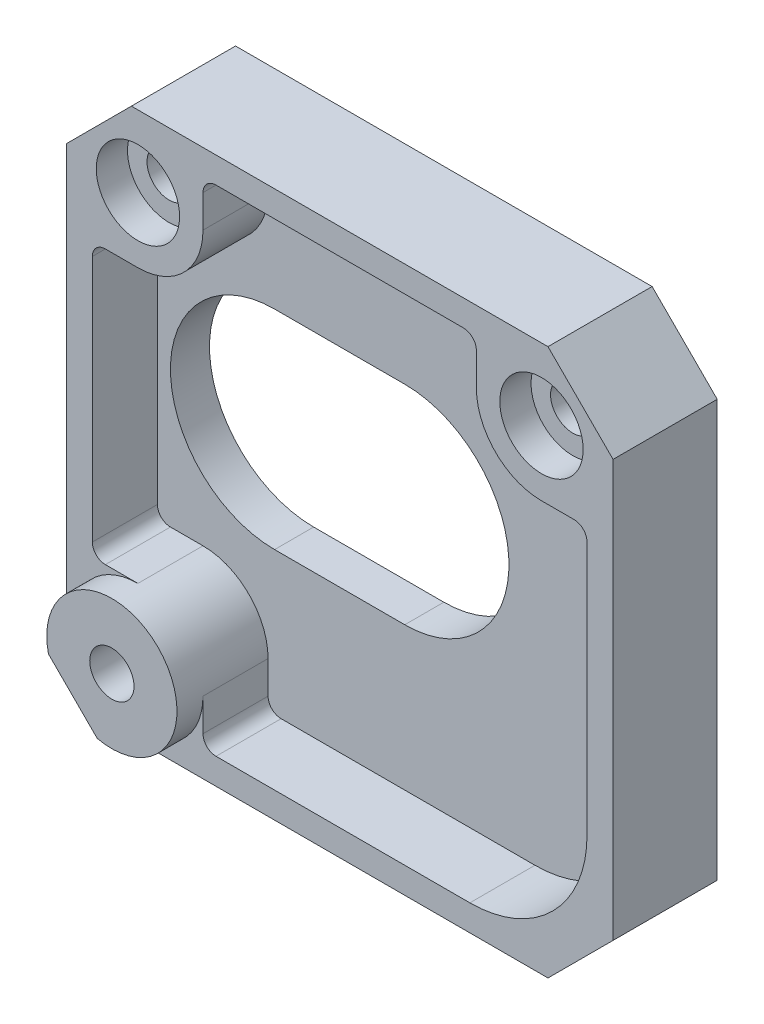
SolidWorks part; units mm, degrees
ref_plane "Спереди" through (0, 0, 0) normal (0, 0, 1) x (1, 0, 0)
ref_plane "Сверху" through (0, 0, 0) normal (0, 1, 0) x (1, 0, 0)
ref_plane "Справа" through (0, 0, 0) normal (1, 0, 0) x (0, 0, -1)
sketch "Эскиз1" plane through (0, 0, 0) normal (0, 0, 1) x (1, 0, 0)
  line L0 (0, 0) -> (-10, 0) construction
  line L1 (21, -21) -> (-21, -21)
  line L2 (21, -21) -> (21, 21)
  line L3 (21, 21) -> (-21, 21)
  line L4 (-21, -21) -> (-21, 21)
  line L5 (21, -21) -> (-21, 21) construction
  line L6 (21, 21) -> (-21, -21) construction
  line L7 (0, -8) -> (-10, -8)
  line L8 (0, 8) -> (-10, 8)
  circle A0 centre (-15.5, -15.5) radius 1.7
  circle A1 centre (-15.5, 15.5) radius 1.7
  circle A2 centre (15.5, 15.5) radius 1.7
  arc A3 (0, -8) -> (0, 8) centre (0, 0) ccw
  arc A4 (-10, 8) -> (-10, -8) centre (-10, 0) ccw
  point P0 (0, 0)
  point P10 (-5, 0)
  point P15 (0, 0)
  point P20 (8, 0)
  point P21 (12.7378, -4.4825)
  point P22 (0, 0)
  point P23 (15.5, 15.5)
  dimension "D3" = 3.4
  dimension "D1" = 42
  dimension "D2" = 42
  dimension "D4" = 15.5
  dimension "D6" = 8
  dimension "D7" = 10
  dimension "D5" = 3
extrude "Бобышка-Вытянуть1" add sketch "Эскиз1" along normal blind 8
chamfer "Фаска1" distance 5 angle 45 4 edges at (-21, -21, 4) (21, -21, 4) (21, 21, 4) (-21, 21, 4)
sketch "Эскиз2" plane through (0, 0, 8) normal (0, 0, 1) x (1, 0, 0)
  line L16 (-10.5, 15.5) -> (-10.5, 19)
  line L17 (-15.5, 10.5) -> (-19, 10.5)
  line L18 (0, 0) -> (0, 19) construction
  line L19 (0, 0) -> (-19, 0) construction
  line L20 (-10.5, -15.5) -> (-10.5, -19)
  line L21 (-15.5, -10.5) -> (-19, -10.5)
  line L22 (10.5, 15.5) -> (10.5, 19)
  line L23 (15.5, 10.5) -> (19, 10.5)
  line L24 (-19, -15.1716) -> (-15.1716, -19)
  line L25 (-15.1716, -19) -> (15.1716, -19)
  line L26 (15.1716, -19) -> (19, -15.1716)
  line L27 (19, -15.1716) -> (19, 15.1716)
  line L28 (19, 15.1716) -> (15.1716, 19)
  line L29 (15.1716, 19) -> (-15.1716, 19)
  line L30 (-15.1716, 19) -> (-19, 15.1716)
  line L31 (-19, 15.1716) -> (-19, -15.1716)
  line L32 (0, 0) -> (18.5, -18.5) construction
  line L33 (-10.5, -19) -> (10, -19)
  line L34 (-21, -16) -> (-16, -21) construction
  line L35 (19, -10) -> (19, 10.5)
  line L36 (16, -21) -> (21, -16) construction
  line L37 (10.5, 19) -> (-10.5, 19)
  line L39 (-19, 10.5) -> (-19, -10.5)
  arc A0 (-15.5, 10.5) -> (-10.5, 15.5) centre (-15.5, 15.5) ccw
  arc A1 (-15.5, -10.5) -> (-10.5, -15.5) centre (-15.5, -15.5) cw
  arc A2 (15.5, 10.5) -> (10.5, 15.5) centre (15.5, 15.5) cw
  arc A3 (10, -19) -> (19, -10) centre (10, -10) ccw
  dimension "D2" = 10
  dimension "D3" = 18
  dimension "D1" = 2
extrude "Вырез-Вытянуть1" cut sketch "Эскиз2" against normal blind 5
sketch "Эскиз3" plane through (0, 0, 8) normal (0, 0, 1) x (1, 0, 0)
  line L0 (-20.3708, -16.6292) -> (-16.6292, -20.3708)
  line L1 (-21, -16) -> (-16, -21) construction
  arc A0 (-16.6292, -20.3708) -> (-20.3708, -16.6292) centre (-15.5, -15.5) ccw
  arc A1 (-10.5, -15.5) -> (-15.5, -10.5) centre (-15.5, -15.5) ccw construction
  circle A2 centre (-15.5, -15.5) radius 1.7
  circle A3 centre (-15.5, -15.5) radius 1.7 construction
extrude "Бобышка-Вытянуть2" add sketch "Эскиз3" along normal blind 2
sketch "Эскиз4" plane through (0, 0, 8) normal (0, 0, 1) x (1, 0, 0)
  circle A0 centre (-15.5, 15.5) radius 3.2
  circle A1 centre (15.5, 15.5) radius 3.2
  dimension "D1" = 6.4
extrude "Вырез-Вытянуть2" cut sketch "Эскиз4" against normal blind 2.4
sketch "Эскиз5" plane through (0, 0, 0) normal (0, 0, -1) x (-1, 0, 0)
  circle A0 centre (-15.5, 15.5) radius 3.4
  circle A1 centre (15.5, 15.5) radius 3.4
  circle A2 centre (15.5, -15.5) radius 3.4
  dimension "D1" = 6.8
extrude "Вырез-Вытянуть3" cut sketch "Эскиз5" against normal blind 2.4
fillet "Скругление1" radius 1 6 edges at (-10.5, -19, 5.5) (-19, -10.5, 5.5) (-19, 10.5, 5.5) (19, 10.5, 5.5) (10.5, 19, 5.5) (-10.5, 19, 5.5)
